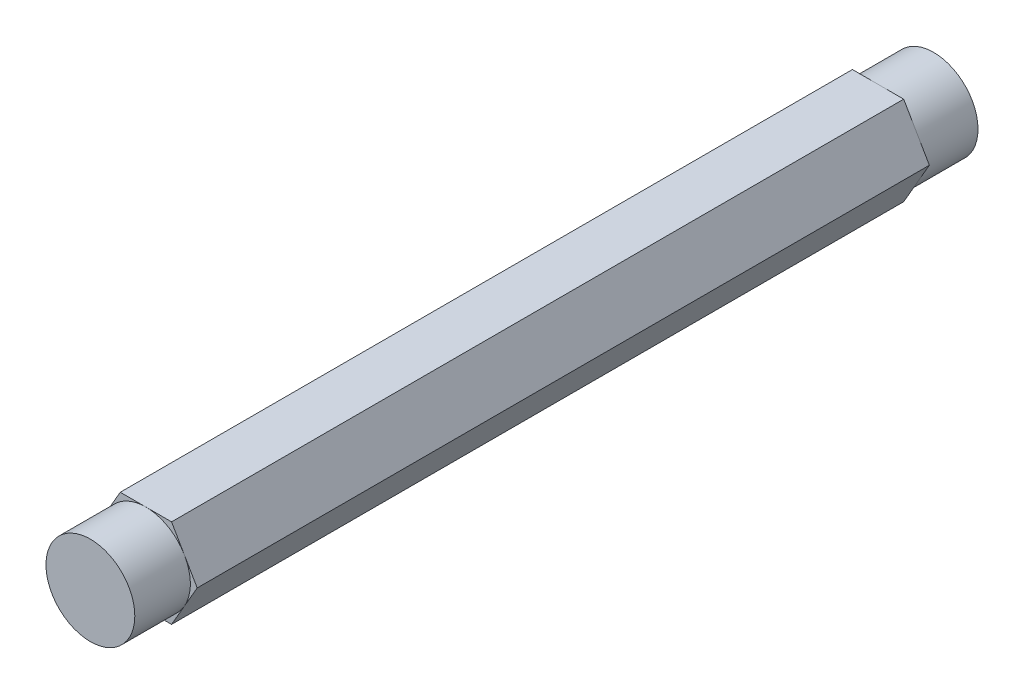
SolidWorks part; units mm, degrees
material "Alloy Steel"
ref_plane "Front Plane" through (0, 0, 0) normal (0, 0, 1) x (1, 0, 0)
ref_plane "Top Plane" through (0, 0, 0) normal (0, 1, 0) x (1, 0, 0)
ref_plane "Right Plane" through (0, 0, 0) normal (1, 0, 0) x (0, 0, -1)
sketch "Sketch1" plane through (0, 0, 0) normal (0, 0, 1) x (1, 0, 0)
  circle A0 centre (0, 0) radius 6.35
  dimension "D1" = 12.7
extrude "Boss-Extrude1" add sketch "Sketch1" along normal blind 7.9375
sketch "Sketch2" plane through (0, 0, 7.9375) normal (0, 0, 1) x (1, 0, 0)
  line L1 (7.3323, 0) -> (3.6662, 6.35)
  line L2 (3.6662, 6.35) -> (-3.6662, 6.35)
  line L3 (-3.6662, 6.35) -> (-7.3323, 0)
  line L4 (-7.3323, 0) -> (-3.6662, -6.35)
  line L5 (-3.6662, -6.35) -> (3.6662, -6.35)
  line L6 (3.6662, -6.35) -> (7.3323, 0)
  circle A0 centre (0, 0) radius 6.35 construction
  dimension "D1" = 12.7
extrude "Boss-Extrude2" add sketch "Sketch2" along normal blind 104.6734
sketch "Sketch3" plane through (0, 0, 112.6109) normal (0, 0, 1) x (1, 0, 0)
  circle A0 centre (0, 0) radius 6.35
  dimension "D1" = 12.7
extrude "Boss-Extrude3" add sketch "Sketch3" along normal blind 7.9375
